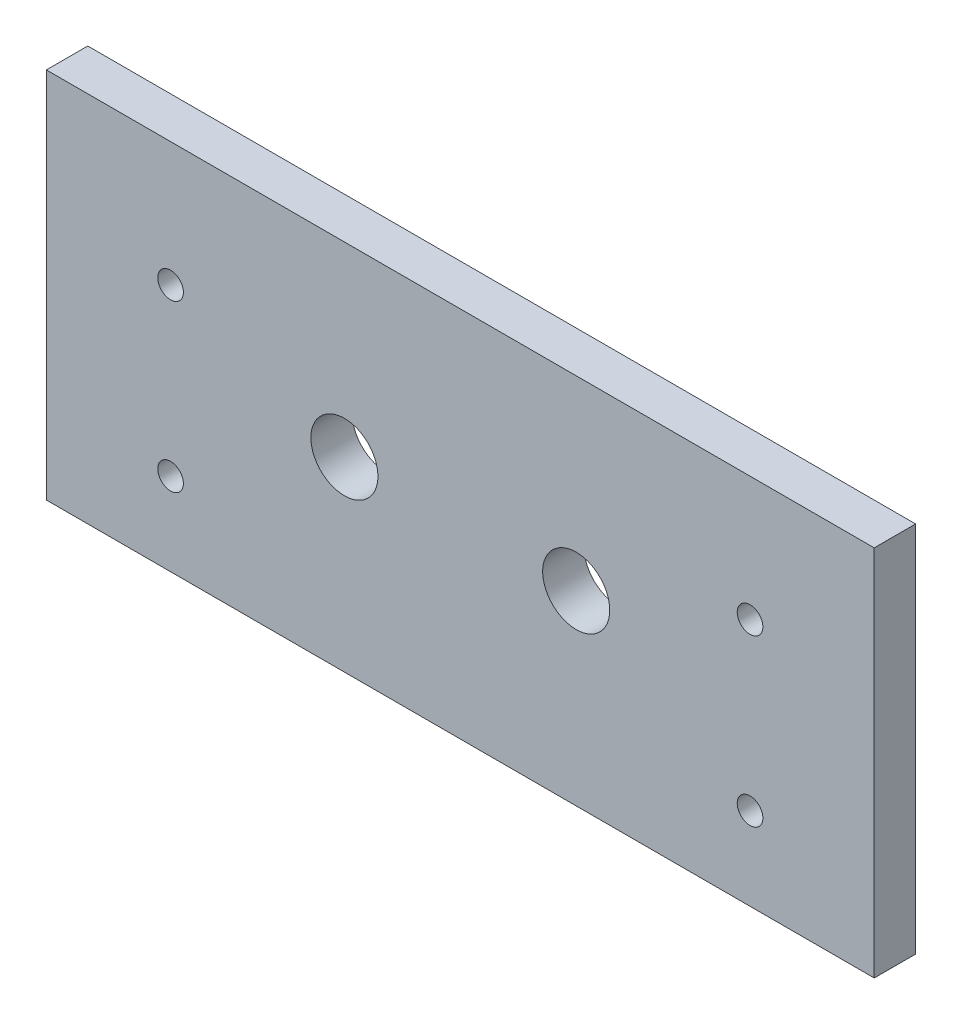
SolidWorks part; units mm, degrees
ref_plane "Plan de face" through (0, 0, 0) normal (0, 0, 1) x (1, 0, 0)
ref_plane "Plan de dessus" through (0, 0, 0) normal (0, 1, 0) x (1, 0, 0)
ref_plane "Plan de droite" through (0, 0, 0) normal (1, 0, 0) x (0, 0, -1)
sketch "Esquisse1" plane through (0, 0, 0) normal (0, 0, 1) x (1, 0, 0)
  line L0 (0, 0) -> (0, 16.8216) construction
  line L1 (-50, -22.5) -> (50, -22.5)
  line L2 (-50, -22.5) -> (-50, 22.5)
  line L3 (-50, 22.5) -> (50, 22.5)
  line L4 (50, -22.5) -> (50, 22.5)
  line L5 (-50, -22.5) -> (50, 22.5) construction
  line L6 (-50, 22.5) -> (50, -22.5) construction
  line L7 (0, 0) -> (42.1574, 0) construction
  circle A0 centre (-35, -12.5) radius 1.55
  circle A2 centre (35, -12.5) radius 1.55
  circle A7 centre (14, 0) radius 4.05
  circle A8 centre (-14, 0) radius 4.05
  circle A11 centre (-35, 7.5) radius 1.55
  circle A13 centre (35, 7.5) radius 1.55
  point P0 (0, 0)
  dimension "D3" = 3.1
  dimension "D6" = 8.1
  dimension "D7" = 14
  dimension "D8" = 3.1
  dimension "D1" = 100
  dimension "D2" = 45
  dimension "D4" = 15
  dimension "D5" = 10
  dimension "D9" = 15
  dimension "D10" = 15
extrude "Boss.-Extru.1" add sketch "Esquisse1" against normal blind 5
